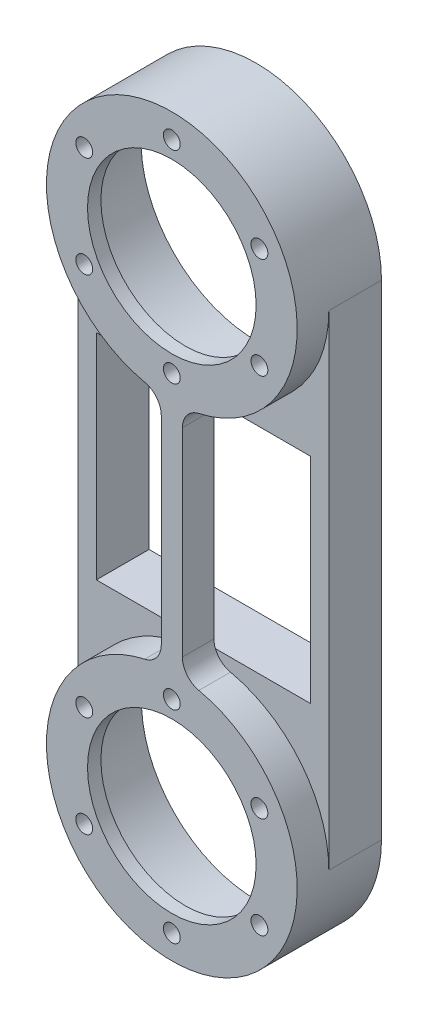
SolidWorks part; units mm, degrees
material "6061-T6 (SS)"
ref_plane "Front Plane" through (0, 0, 0) normal (0, 0, 1) x (1, 0, 0)
ref_plane "Top Plane" through (0, 0, 0) normal (0, 1, 0) x (1, 0, 0)
ref_plane "Right Plane" through (0, 0, 0) normal (1, 0, 0) x (0, 0, -1)
sketch "Sketch1" plane through (0, 0, 0) normal (0, 0, 1) x (1, 0, 0)
  line L0 (-29.75, 57.5) -> (-29.75, -57.5)
  line L1 (29.75, -57.5) -> (29.75, 57.5)
  line L2 (0, -57.5) -> (0, 57.5) construction
  line L3 (-29.75, 0) -> (29.75, 0) construction
  line L4 (0, 57.5) -> (0, 87.25) construction
  line L15 (-29.75, 57.5) -> (27.5, 57.5) construction
  line L31 (-25.4, -25.4) -> (25.4, 25.4) construction
  line L32 (-25.4, 25.4) -> (25.4, -25.4) construction
  circle A2 centre (0, 57.5) radius 27.5
  circle A3 centre (0, -57.5) radius 27.5
  arc A6 (29.75, 57.5) -> (-29.75, 57.5) centre (0, 57.5) ccw
  arc A7 (29.75, -57.5) -> (-29.75, -57.5) centre (0, -57.5) cw
  point P34 (0, 0)
  dimension "D2" = 59.5
  dimension "D4" = 55
  dimension "D1" = 115
  dimension "D9" = 50.8
  dimension "D10" = 50.8
extrude "Boss-Extrude1" add sketch "Sketch1" along normal blind 20
sketch "Sketch2" plane through (0, 0, 20) normal (0, 0, 1) x (1, 0, 0)
  line L0 (-29.75, 0) -> (29.75, 0) construction
  line L1 (-27.5, 57.5) -> (27.5, 57.5) construction
  line L2 (-29.75, 57.5) -> (-29.75, -57.5)
  line L3 (29.75, -57.5) -> (29.75, 57.5)
  line L4 (-29.75, 57.5) -> (-29.75, -57.5)
  line L5 (29.75, -57.5) -> (29.75, 57.5)
  circle A0 centre (0, 57.5) radius 20
  circle A2 centre (0, 57.5) radius 27.5 construction
  circle A6 centre (0, 57.5) radius 24 construction
  circle A7 centre (0, 81.5) radius 2
  circle A8 centre (20.7846, 69.5) radius 2
  circle A9 centre (20.7846, 45.5) radius 2
  circle A10 centre (0, 33.5) radius 2
  circle A11 centre (-20.7846, 45.5) radius 2
  circle A12 centre (-20.7846, 69.5) radius 2
  circle A13 centre (0, -57.5) radius 24 construction
  circle A14 centre (-20.7846, -69.5) radius 2
  circle A15 centre (-20.7846, -45.5) radius 2
  circle A16 centre (0, -33.5) radius 2
  circle A17 centre (20.7846, -45.5) radius 2
  circle A18 centre (20.7846, -69.5) radius 2
  circle A19 centre (0, -81.5) radius 2
  circle A20 centre (0, -57.5) radius 20
  arc A22 (29.75, 57.5) -> (-29.75, 57.5) centre (0, 57.5) ccw
  arc A23 (29.75, 57.5) -> (-29.75, 57.5) centre (0, 57.5) ccw
  arc A24 (-29.75, -57.5) -> (29.75, -57.5) centre (0, -57.5) ccw
  arc A25 (-29.75, -57.5) -> (29.75, -57.5) centre (0, -57.5) ccw
  point P25 (0, 57.5)
  point P37 (0, -57.5)
  point P44 (0, 0)
  dimension "D2" = 40
  dimension "D3" = 48
  dimension "D4" = 4
  dimension "D1" = 0
  dimension "D5" = 6
extrude "Boss-Extrude2" add sketch "Sketch2" against normal blind 3.175
sketch "Sketch4" [suppressed] plane through (0, 63.5, 0) normal (0, 1, 0) x (1, 0, 0)
  line L0 (-13.175, -4.7625) -> (18.175, -4.7625) construction
  line L3 (0, 0.4369) -> (0, -9.525) construction
  line L4 (30.675, -9.525) -> (-30.675, -9.525) construction
  line L5 (-30.675, -9.525) -> (-30.675, 0) construction
  circle A0 centre (-20.675, -4.7625) radius 2.5
  circle A1 centre (20.675, -4.7625) radius 2.5
  dimension "D1" = 5
  dimension "D2" = 10
sketch "Sketch7" [suppressed] plane through (0, 0, 0) normal (0, 0, -1) x (-1, 0, 0)
  line L0 (-27.5, 32.2375) -> (-27.5, 12.6232)
  line L1 (-30.675, -12.6232) -> (-27.5, -12.6232)
  line L2 (27.5, -32.2375) -> (27.5, -12.6232)
  line L3 (30.675, -12.6232) -> (30.675, 12.6232)
  line L4 (30.675, 12.6232) -> (27.5, 12.6232)
  line L5 (-30.675, 12.6232) -> (-30.675, -12.6232)
  line L6 (-27.5, -12.6232) -> (-27.5, -32.2375)
  line L7 (-27.5, 12.6232) -> (-30.675, 12.6232)
  line L8 (27.5, 12.6232) -> (27.5, 32.2375)
  line L9 (27.5, -12.6232) -> (30.675, -12.6232)
  circle A0 centre (0, -32.2375) radius 27.5 construction
  circle A1 centre (0, 32.2375) radius 27.5 construction
  arc A2 (-27.5, -32.2375) -> (27.5, -32.2375) centre (0, -32.2375) ccw
  arc A3 (27.5, 32.2375) -> (-27.5, 32.2375) centre (0, 32.2375) ccw
extrude "Cut-Extrude4" [suppressed] cut sketch "Sketch7" against normal up to surface (6.35 mm away)
fillet "Fillet3" [suppressed] radius 5
extrude "Cut-Extrude5" [suppressed] cut sketch "Sketch4" against normal blind 10
mirror "Mirror1" [suppressed] about plane through (0, 0, 0) normal (0, 1, 0)
sketch "Sketch8" plane through (0, 0, 0) normal (0, 0, -1) x (-1, 0, 0)
  line L0 (-29.75, 0) -> (29.75, 0) construction
  line L1 (-29.75, -57.5) -> (-29.75, 57.5) construction
  line L2 (29.75, 57.5) -> (29.75, -57.5) construction
  line L3 (-2.5, -27.8552) -> (-2.5, 27.8552)
  line L4 (0, 57.5) -> (0, 0) construction
  line L5 (2.5, -27.8552) -> (2.5, 27.8552)
  line L6 (-29.75, -57.5) -> (-29.75, 57.5)
  line L7 (29.75, 57.5) -> (29.75, -57.5)
  arc A0 (2.5, 27.8552) -> (29.75, 57.5) centre (0, 57.5) ccw
  arc A1 (2.5, -27.8552) -> (29.75, -57.5) centre (0, -57.5) cw
  arc A2 (-29.75, -57.5) -> (-2.5, -27.8552) centre (0, -57.5) cw
  arc A3 (-29.75, 57.5) -> (-2.5, 27.8552) centre (0, 57.5) ccw
  point P15 (-2.5, 0)
  point P17 (2.5, 0)
  dimension "D1" = 2.5
extrude "Cut-Extrude6" cut sketch "Sketch8" against normal blind 44
fillet "Fillet4" radius 5 4 edges at (-2.5, -27.8552, 10) (-2.5, 27.8552, 10) (2.5, 27.8552, 10) (2.5, -27.8552, 10)
sketch "Sketch9" plane through (0, 0, 0) normal (0, 0, 1) x (1, 0, 0)
  line L0 (-76.2484, 0) -> (52.6847, 0) construction
  line L1 (-29.75, 57.5) -> (-29.75, -57.5)
  line L2 (29.75, 57.5) -> (29.75, -57.5)
  arc A0 (6.4209, 28.4512) -> (-6.4209, 28.4512) centre (0, 57.5) ccw construction
  arc A1 (29.75, 57.5) -> (-29.75, 57.5) centre (0, 57.5) ccw
  arc A2 (29.75, -57.5) -> (-29.75, -57.5) centre (0, -57.5) cw
  circle A3 centre (0, 57.5) radius 27.3026
  circle A4 centre (0, -57.5) radius 27.2017
  point P9 (-29.75, 0)
  point P13 (29.75, 0)
extrude "Boss-Extrude3" add sketch "Sketch9" along normal blind 12.5
sketch "Sketch10" plane through (0, 0, 0) normal (1, 0, 0) x (0, 0, -1)
  line L0 (0, 0) -> (-61.1161, 0) construction
  line L1 (0, -57.5) -> (0, 57.5) construction
  line L2 (-20, 28.4512) -> (-20, -28.4512) construction
  circle A0 centre (-61.1161, 0) radius 50
  dimension "D1" = 100
sketch "Sketch11" plane through (0, 0, 20) normal (0, 0, 1) x (1, 0, 0)
  circle A1 centre (-20.7846, 69.5) radius 2
  circle A2 centre (-20.7846, 69.5) radius 2
  circle A3 centre (-20.7846, -69.5) radius 2
  circle A4 centre (-20.7846, -69.5) radius 2
  circle A5 centre (-20.7846, -45.5) radius 2
  circle A6 centre (-20.7846, -45.5) radius 2
  circle A7 centre (0, -33.5) radius 2
  circle A8 centre (0, -33.5) radius 2
  circle A9 centre (20.7846, -45.5) radius 2
  circle A10 centre (20.7846, -45.5) radius 2
  circle A11 centre (20.7846, -69.5) radius 2
  circle A12 centre (20.7846, -69.5) radius 2
  circle A13 centre (0, -81.5) radius 2
  circle A14 centre (0, -81.5) radius 2
  circle A15 centre (0, -57.5) radius 20
  circle A16 centre (0, -57.5) radius 20
  circle A17 centre (-20.7846, 45.5) radius 2
  circle A18 centre (-20.7846, 45.5) radius 2
  circle A19 centre (0, 33.5) radius 2
  circle A20 centre (0, 33.5) radius 2
  circle A21 centre (20.7846, 45.5) radius 2
  circle A22 centre (20.7846, 45.5) radius 2
  circle A23 centre (20.7846, 69.5) radius 2
  circle A24 centre (20.7846, 69.5) radius 2
  circle A25 centre (0, 81.5) radius 2
  circle A26 centre (0, 81.5) radius 2
  circle A27 centre (0, 57.5) radius 20
  circle A28 centre (0, 57.5) radius 20
  dimension "D1" = 0
  dimension "D2" = 0
  dimension "D3" = 0
  dimension "D4" = 0
  dimension "D5" = 0
  dimension "D6" = 0
  dimension "D7" = 0
  dimension "D8" = 0
  dimension "D9" = 0
  dimension "D10" = 0
  dimension "D11" = 0
  dimension "D12" = 0
  dimension "D13" = 0
  dimension "D14" = 0
sketch "Sketch12" plane through (0, 0, 0) normal (0, 0, -1) x (-1, 0, 0)
  line L1 (-25.4, -25.4) -> (25.4, -25.4)
  line L2 (-25.4, -25.4) -> (-25.4, 25.4)
  line L3 (-25.4, 25.4) -> (25.4, 25.4)
  line L4 (25.4, -25.4) -> (25.4, 25.4)
  line L5 (-25.4, -25.4) -> (25.4, 25.4) construction
  line L6 (-25.4, 25.4) -> (25.4, -25.4) construction
  point P0 (0, 0)
  dimension "D1" = 50.8
  dimension "D2" = 50.8
extrude "Cut-Extrude7" cut sketch "Sketch12" against normal up to surface (12.5 mm away) up to face at (14.3074, 0, 12.5)
equation "\"d\"=5"
equation "\"D2@Sketch12\"=\"D1@Sketch12\""
